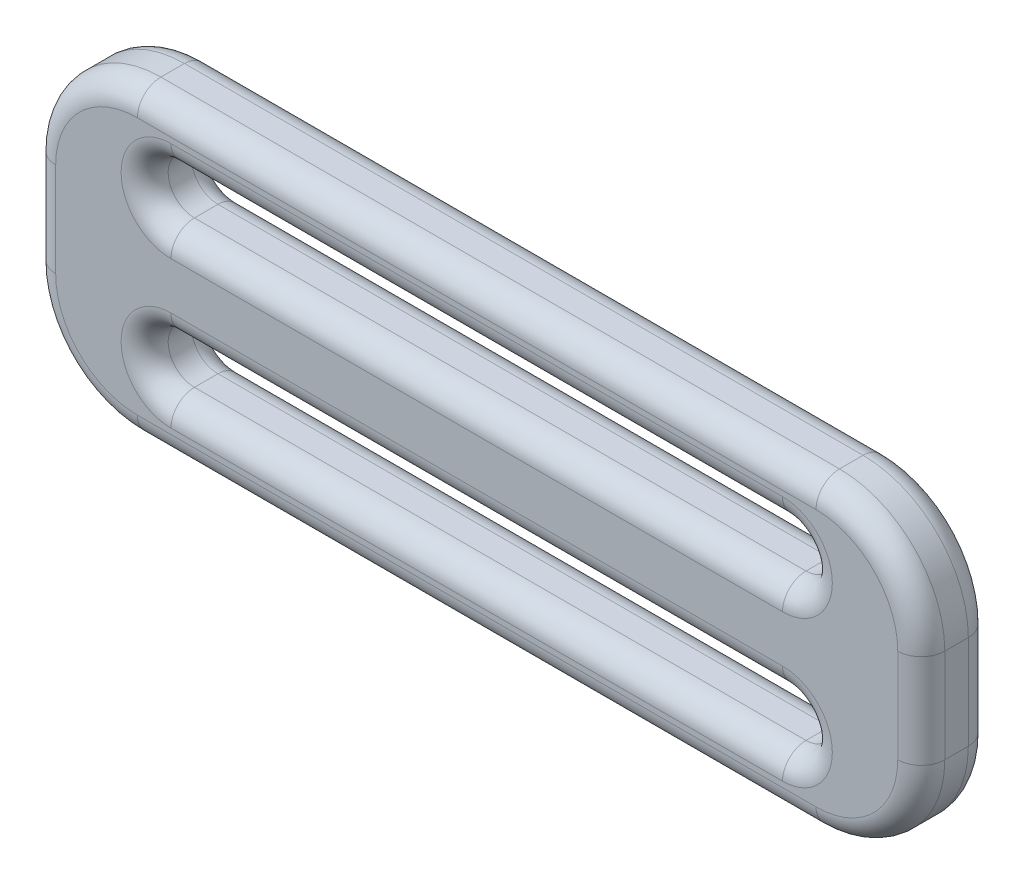
SolidWorks part; units mm, degrees
material "ABS"
ref_plane "Front Plane" through (0, 0, 0) normal (0, 0, 1) x (1, 0, 0)
ref_plane "Top Plane" through (0, 0, 0) normal (0, 1, 0) x (1, 0, 0)
ref_plane "Right Plane" through (0, 0, 0) normal (1, 0, 0) x (0, 0, -1)
ref_plane "Plane1" through (0, 0, 0.6) normal (0, 0, -1) x (-1, 0, 0)
sketch "Sketch1" plane through (0, 0, 0.6) normal (0, 0, -1) x (-1, 0, 0)
  line L0 (-4.4734, 35.787) -> (-33.3266, 35.787)
  line L1 (-37.8, 31.3136) -> (-37.8, 27.3136)
  line L2 (-33.3266, 22.8402) -> (-4.4734, 22.8402)
  line L3 (0, 27.3136) -> (0, 31.3136)
  line L4 (-5.9, 27.3136) -> (-31.9, 27.3136)
  line L5 (-18.9, 22.8402) -> (-18.9, 25.0769) construction
  line L6 (-18.9, 25.0769) -> (-18.9, 27.3136) construction
  line L7 (-18.9, 35.787) -> (-18.9, 28.2965) construction
  line L13 (-5.9, 25.0769) -> (-31.9, 25.0769)
  line L16 (-5.9, 31.3139) -> (-31.9, 31.3139)
  line L17 (-31.9, 33.5505) -> (-5.9, 33.5505)
  arc A0 (0, 31.3136) -> (-4.4734, 35.787) centre (-4.4734, 31.3136) ccw
  arc A1 (-33.3266, 35.787) -> (-37.8, 31.3136) centre (-33.3266, 31.3136) ccw
  arc A2 (-37.8, 27.3136) -> (-33.3266, 22.8402) centre (-33.3266, 27.3136) ccw
  arc A3 (-4.4734, 22.8402) -> (0, 27.3136) centre (-4.4734, 27.3136) ccw
  arc A21 (-5.9, 27.3136) -> (-5.9, 25.0769) centre (-5.9, 26.1953) cw
  arc A22 (-31.9, 25.0769) -> (-31.9, 27.3136) centre (-31.9, 26.1953) cw
  arc A24 (-5.9, 33.5505) -> (-5.9, 31.3139) centre (-5.9, 32.4322) cw
  arc A25 (-31.9, 31.3139) -> (-31.9, 33.5505) centre (-31.9, 32.4322) cw
  point P12 (-18.9, 33.5505)
  dimension "D1" = 37.8
  dimension "D2" = 2.2367
  dimension "D3" = 26
  dimension "D4" = 2.2367
  dimension "D5" = 26
  dimension "D6" = 2.2364
  dimension "D7" = 2.2367
extrude "Boss-Extrude1" add sketch "Sketch1" against normal blind 3
fillet "Fillet1" radius 1 32 edges at (18.9, 35.787, 3.6) (36.4898, 34.4768, 3.6) (37.8, 29.3136, 3.6) (36.4898, 24.1505, 3.6) (18.9, 22.8402, 3.6) (1.3102, 24.1505, 3.6) (0, 29.3136, 3.6) (1.3102, 34.4768, 3.6) (33.0183, 26.1953, 3.6) (18.9, 27.3136, 3.6) (4.7817, 26.1953, 3.6) (18.9, 25.0769, 3.6) (33.0183, 32.4322, 3.6) (18.9, 33.5505, 3.6) (4.7817, 32.4322, 3.6) (18.9, 31.3139, 3.6) (0, 29.3136, 0.6) (1.3102, 24.1505, 0.6) (18.9, 22.8402, 0.6) (36.4898, 24.1505, 0.6) (37.8, 29.3136, 0.6) (36.4898, 34.4768, 0.6) (18.9, 35.787, 0.6) (1.3102, 34.4768, 0.6) (18.9, 27.3136, 0.6) (33.0183, 26.1953, 0.6) (18.9, 25.0769, 0.6) (4.7817, 26.1953, 0.6) (18.9, 33.5505, 0.6) (33.0183, 32.4322, 0.6) (18.9, 31.3139, 0.6) (4.7817, 32.4322, 0.6)
